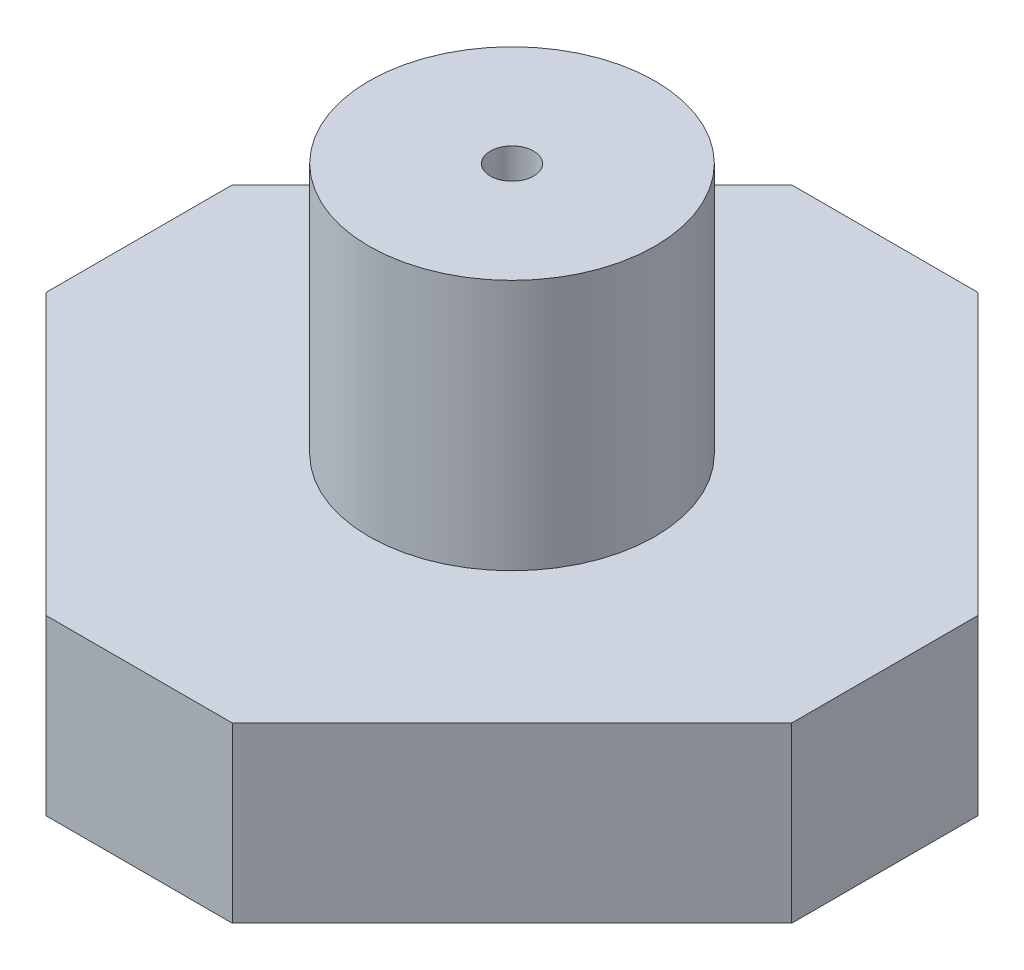
SolidWorks part; units mm, degrees
ref_plane "前视基准面" through (0, 0, 0) normal (0, 0, 1) x (1, 0, 0)
ref_plane "上视基准面" through (0, 0, 0) normal (0, 1, 0) x (1, 0, 0)
ref_plane "右视基准面" through (0, 0, 0) normal (1, 0, 0) x (0, 0, -1)
other "Configuration Table"
sketch "草图1" plane through (0, 0, 0) normal (0, 1, 0) x (1, 0, 0)
  line L0 (-4.3, -1.074) -> (-1.074, -4.3)
  line L1 (-4.3, 1.074) -> (-1.074, 4.3)
  line L2 (1.074, -4.3) -> (4.3, -1.074)
  line L3 (1.074, 4.3) -> (4.3, 1.074)
  line L4 (-5.374, 0) -> (5.374, 0) construction
  line L5 (0, -5.374) -> (0, 5.374) construction
  line L8 (-4.3, 1.074) -> (-4.3, -1.074)
  line L10 (4.3, 1.074) -> (4.3, -1.074)
  line L11 (-1.074, 4.3) -> (1.074, 4.3)
  line L13 (-1.074, -4.3) -> (1.074, -4.3)
  point P1 (0, 0)
  dimension "D1" = 7.6
  dimension "D2" = 8.6
  dimension "D3" = 8.6
extrude "凸台-拉伸1" add sketch "草图1" along normal blind 2
sketch "草图2" plane through (0, 2, 0) normal (0, 1, 0) x (1, 0, 0)
  circle A0 centre (0, 0) radius 1.65
  dimension "D1" = 3.3
extrude "凸台-拉伸2" add sketch "草图2" along normal blind 2.9
sketch "草图3" plane through (0, 0, 0) normal (0, -1, 0) x (1, 0, 0)
  circle A0 centre (0, 0) radius 0.25
  dimension "D1" = 0.5
extrude "切除-拉伸1" cut sketch "草图3" against normal blind 10
